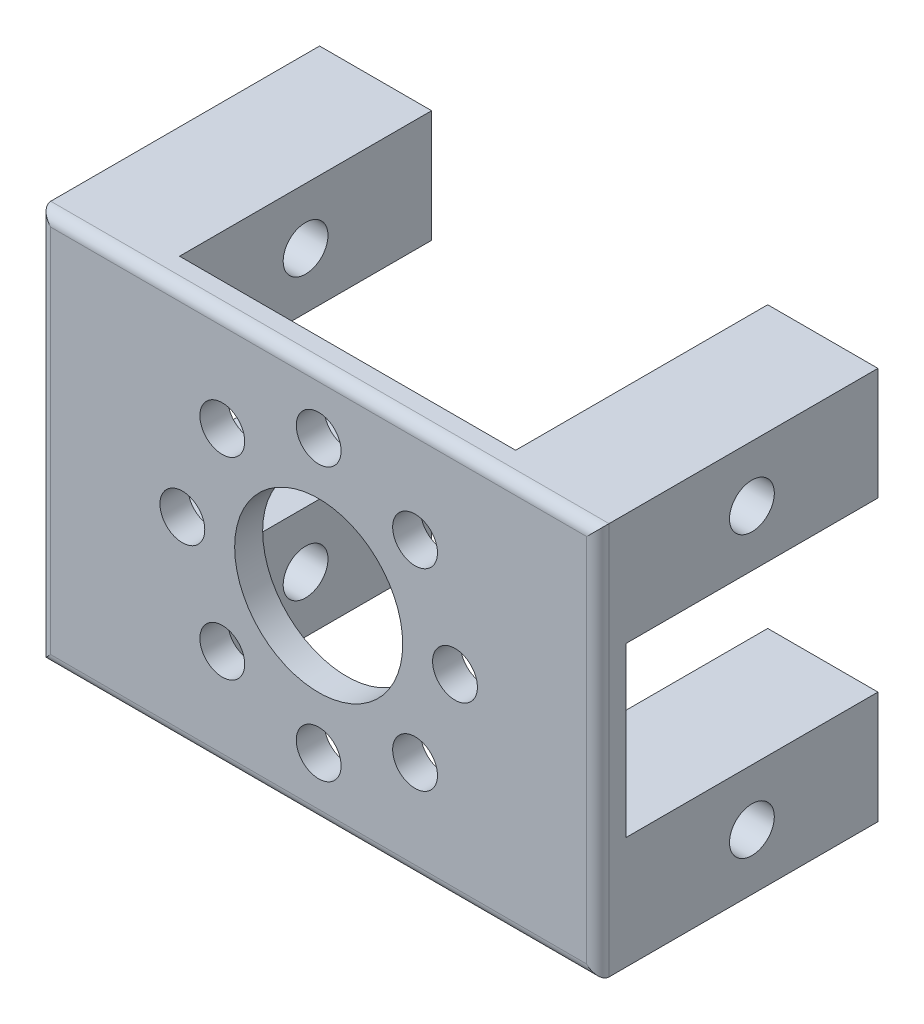
SolidWorks part; units mm, degrees
ref_plane "Plano frontal" through (0, 0, 0) normal (0, 0, 1) x (1, 0, 0)
ref_plane "Plano superior" through (0, 0, 0) normal (0, 1, 0) x (1, 0, 0)
ref_plane "Plano direito" through (0, 0, 0) normal (1, 0, 0) x (0, 0, -1)
sketch "Esboço1" plane through (0, 0, 0) normal (0, 0, 1) x (1, 0, 0)
  line L1 (-49.8392, -35.0451) -> (49.8392, -35.0451)
  line L2 (-49.8392, -35.0451) -> (-49.8392, 35.0451)
  line L3 (-49.8392, 35.0451) -> (49.8392, 35.0451)
  line L4 (49.8392, -35.0451) -> (49.8392, 35.0451)
  line L5 (-49.8392, -35.0451) -> (49.8392, 35.0451) construction
  line L6 (-49.8392, 35.0451) -> (49.8392, -35.0451) construction
  circle A0 centre (0, 0) radius 15
  circle A1 centre (24.3351, 0) radius 4
  circle A2 centre (17.2075, -17.2075) radius 4
  circle A3 centre (0, -24.3351) radius 4
  circle A4 centre (-17.2075, -17.2075) radius 4
  circle A5 centre (-24.3351, 0) radius 4
  circle A6 centre (-17.2075, 17.2075) radius 4
  circle A7 centre (0, 24.3351) radius 4
  circle A8 centre (17.2075, 17.2075) radius 4
  point P0 (0, 0)
  dimension "D1" = 8
extrude "Ressalto-extrusão1" add sketch "Esboço1" along normal blind 50
sketch "Esboço2" plane through (0, 0, 0) normal (0, 1, 0) x (1, 0, 0)
  line L5 (-29.8392, 0) -> (30.1608, 0)
  line L6 (-29.8392, 0) -> (-29.8392, -45)
  line L7 (-29.8392, -45) -> (30.1608, -45)
  line L8 (30.1608, 0) -> (30.1608, -45)
  point P4 (0, 0)
  point P5 (0, 0)
  point P6 (0, 0)
  point P7 (0, 0)
  point P8 (0, 0)
  point P9 (0, 0)
  point P10 (0, 0)
  dimension "D1" = 60
extrude "Corte-extrusão1" cut sketch "Esboço2" against normal through all both and the other way through all contours L6 L5 L8 L7
sketch "Esboço3" plane through (0, 0, 0) normal (1, 0, 0) x (0, 0, -1)
  line L0 (0, 0) -> (0, 15)
  line L1 (0, 35.0451) -> (0, -35.0451) construction
  line L2 (0, 15) -> (-45, 15)
  line L3 (-45, 15) -> (-45, -15)
  line L4 (-45, -15) -> (0, -15)
  line L5 (0, -13.2075) -> (0, -21.2075) construction
  line L6 (0, -15) -> (0, 0)
  dimension "D1" = 15
  dimension "D2" = 45
  dimension "D3" = 30
extrude "Corte-extrusão2" cut sketch "Esboço3" against normal through all both and the other way through all contours L6 L0 L2 L3 L4
sketch "Esboço4" plane through (0, 0, 0) normal (1, 0, 0) x (0, 0, -1)
  circle A0 centre (-22.5, -25.0225) radius 4
  circle A1 centre (-22.5, 25.0225) radius 4
extrude "Corte-extrusão4" cut sketch "Esboço4" against normal through all both and the other way through all
fillet "Filete4" radius 2 4 edges at (49.8392, 0, 50) (0, -35.0451, 50) (-49.8392, 0, 50) (0, 35.0451, 50)
